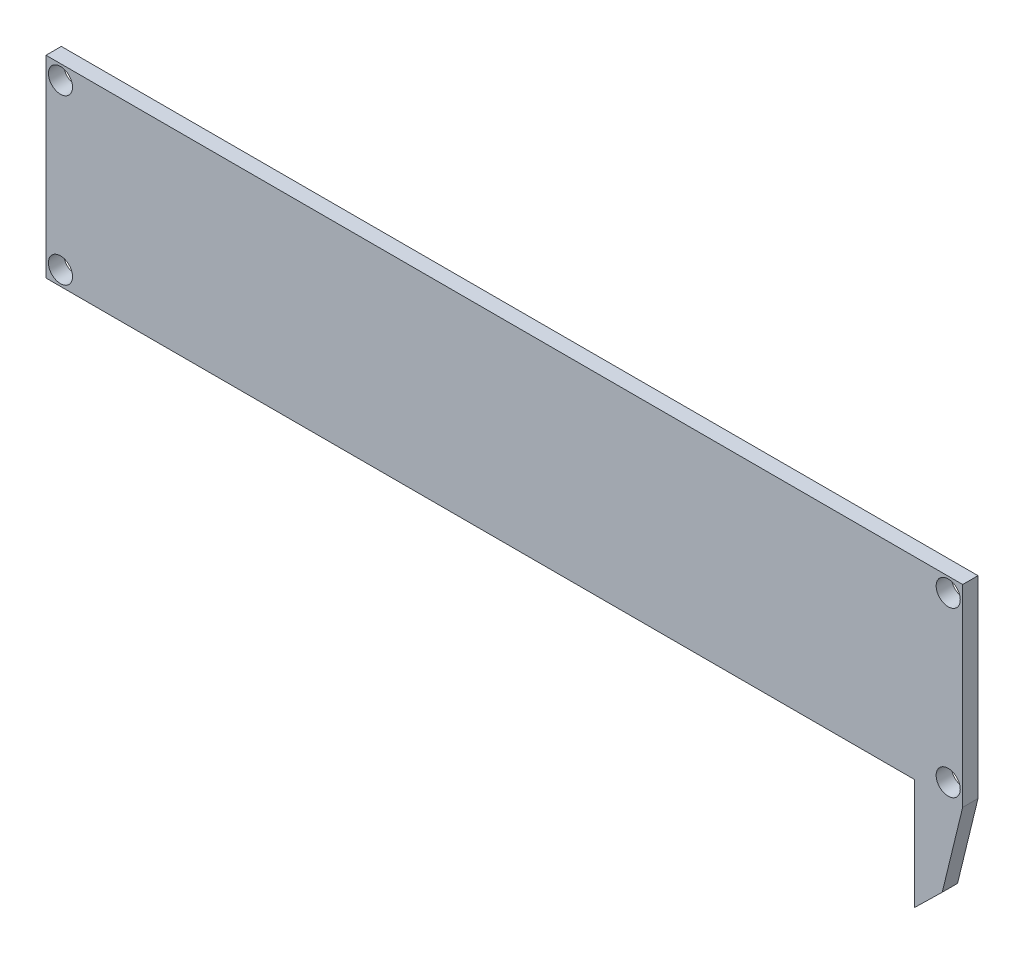
SolidWorks part; units mm, degrees
ref_plane "Front Plane" through (0, 0, 0) normal (0, 0, 1) x (1, 0, 0)
ref_plane "Top Plane" through (0, 0, 0) normal (0, 1, 0) x (1, 0, 0)
ref_plane "Right Plane" through (0, 0, 0) normal (1, 0, 0) x (0, 0, -1)
sketch "Sketch1" plane through (0, 0, 0) normal (0, 0, 1) x (1, 0, 0)
  line L1 (0, 0) -> (190, 0)
  line L2 (0, 0) -> (0, 40)
  line L3 (0, 40) -> (190, 40)
  line L4 (190, 0) -> (190, 40)
  dimension "D1" = 40
  dimension "D2" = 190
extrude "Boss-Extrude1" add sketch "Sketch1" along normal blind 3.175
sketch "Sketch6" plane through (0, 0, 3.175) normal (0, 0, 1) x (1, 0, 0)
  line L0 (190, 40) -> (0, 40) construction
  line L1 (0, 40) -> (0, 0) construction
  line L2 (190, 0) -> (190, 40) construction
  line L3 (0, 0) -> (190, 0) construction
  circle A0 centre (3, 37) radius 2.5
  circle A1 centre (3, 3) radius 2.5
  circle A2 centre (187, 37) radius 2.5
  circle A3 centre (187, 3) radius 2.5
  dimension "D2" = 3
  dimension "D5" = 3
  dimension "D1" = 3
  dimension "D6" = 3
  dimension "D7" = 3
  dimension "D3" = 2
  dimension "D4" = 2
extrude "Cut-Extrude2" cut sketch "Sketch6" against normal through all
sketch "Sketch8" plane through (0, 0, 3.175) normal (0, 0, 1) x (1, 0, 0)
  line L0 (180, -23) -> (185.7647, -17.3601)
  line L1 (190, 0) -> (180, 0)
  line L2 (185.7647, -17.3601) -> (190, 0)
  line L4 (180, 0) -> (180, -23)
  dimension "D1" = 10
  dimension "D2" = 23
extrude "Boss-Extrude2" add sketch "Sketch8" against normal up to surface (3.175 mm away) up to face at (189.5, 3, 0)
